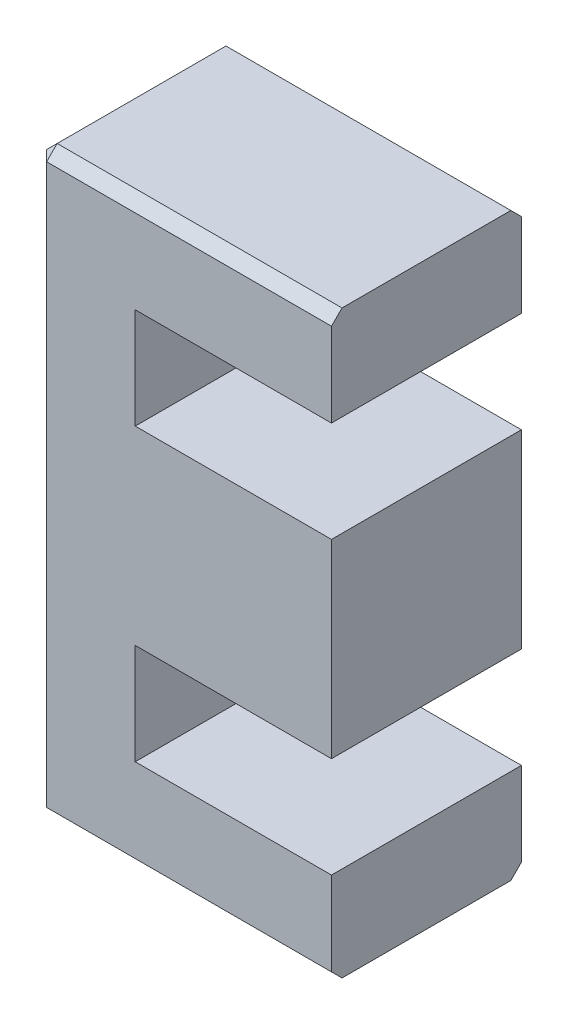
SolidWorks part; units mm, degrees
ref_plane "Front Plane" through (0, 0, 0) normal (0, 0, 1) x (1, 0, 0)
ref_plane "Top Plane" through (0, 0, 0) normal (0, 1, 0) x (1, 0, 0)
ref_plane "Right Plane" through (0, 0, 0) normal (1, 0, 0) x (0, 0, -1)
sketch "Sketch1" plane through (0, 0, 0) normal (0, 0, 1) x (1, 0, 0)
  line L0 (0, 84.5208) -> (0, -91.5495) construction
  line L1 (-56.7572, 0) -> (49.0256, 0) construction
  line L2 (28, 55) -> (-28, 55)
  line L3 (-28, 55) -> (-28, -55)
  line L4 (28, 55) -> (28, 37.1)
  line L5 (28, 37.1) -> (-9.2, 37.1)
  line L6 (-9.2, 37.1) -> (-9.2, 18)
  line L7 (-9.2, 18) -> (28, 18)
  line L8 (28, 18) -> (28, -18)
  line L9 (-9.2, -18) -> (28, -18)
  line L10 (-9.2, -37.1) -> (-9.2, -18)
  line L11 (28, -37.1) -> (-9.2, -37.1)
  line L12 (28, -55) -> (28, -37.1)
  line L13 (28, -55) -> (-28, -55)
  point P7 (0, 55)
  point P15 (28, 0)
  point P16 (-28, 0)
  dimension "D1" = 110
  dimension "D2" = 74.2
  dimension "D3" = 36
  dimension "D4" = 56
  dimension "D5" = 37.2
extrude "Boss-Extrude1" add sketch "Sketch1" along normal mid plane 36
chamfer "Chamfer1" distance 2 angle 45 8 edges at (0, 55, 18) (0, -55, -18) (0, -55, 18) (-28, -55, 0) (-28, 0, 18) (-28, 0, -18) (0, 55, -18) (-28, 55, 0)
